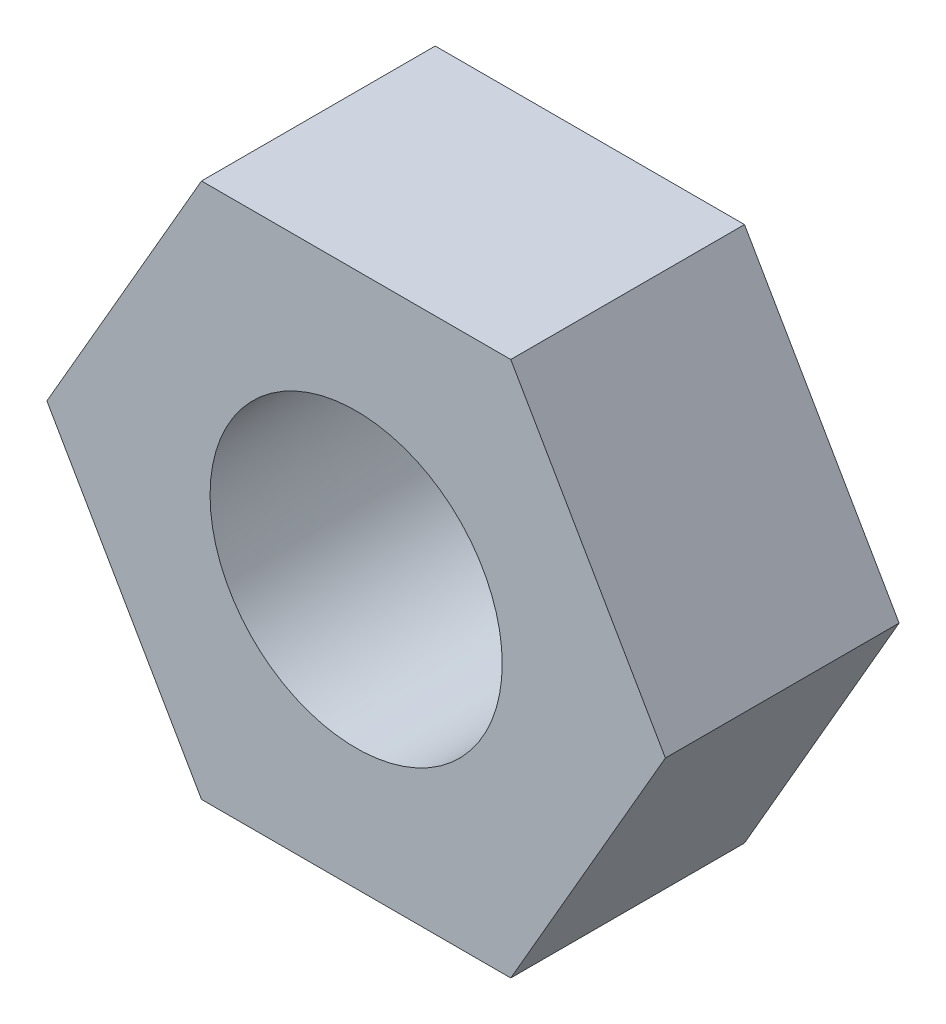
SolidWorks part; units mm, degrees
ref_plane "Front Plane" through (0, 0, 0) normal (0, 0, 1) x (1, 0, 0)
ref_plane "Top Plane" through (0, 0, 0) normal (0, 1, 0) x (1, 0, 0)
ref_plane "Right Plane" through (0, 0, 0) normal (1, 0, 0) x (0, 0, -1)
sketch "Across_flats_5.5" plane through (0, 0, 0) normal (0, 0, 1) x (1, 0, 0)
  line L0 (3.1754, 0) -> (1.5877, 2.75)
  line L1 (1.5877, 2.75) -> (-1.5877, 2.75)
  line L2 (-1.5877, 2.75) -> (-3.1754, 0)
  line L3 (-3.1754, 0) -> (-1.5877, -2.75)
  line L4 (-1.5877, -2.75) -> (1.5877, -2.75)
  line L5 (1.5877, -2.75) -> (3.1754, 0)
  circle A0 centre (0, 0) radius 1.5
  dimension "D1" = 3
extrude "Nut_thread_envelope_height_2.4" add sketch "Across_flats_5.5" along normal blind 2.4
